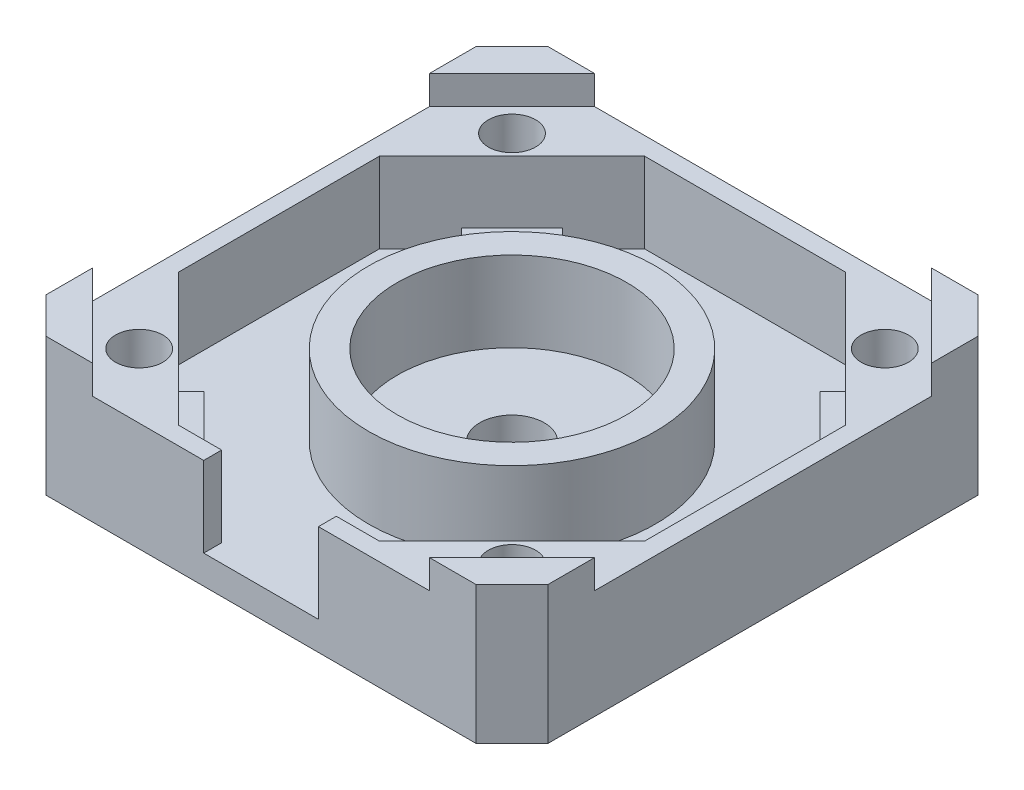
SolidWorks part; units mm, degrees
ref_plane "Front Plane" through (0, 0, 0) normal (0, 0, 1) x (1, 0, 0)
ref_plane "Top Plane" through (0, 0, 0) normal (0, 1, 0) x (1, 0, 0)
ref_plane "Right Plane" through (0, 0, 0) normal (1, 0, 0) x (0, 0, -1)
sketch "Sketch1" plane through (0, 0, 0) normal (0, 1, 0) x (1, 0, 0)
  line L1 (-17.5, -17.5) -> (17.5, -17.5)
  line L2 (-17.5, -17.5) -> (-17.5, 17.5)
  line L3 (-17.5, 17.5) -> (17.5, 17.5)
  line L4 (17.5, -17.5) -> (17.5, 17.5)
  line L5 (-17.5, -17.5) -> (17.5, 17.5) construction
  line L6 (-17.5, 17.5) -> (17.5, -17.5) construction
  point P0 (0, 0)
  dimension "D1" = 35
  dimension "D2" = 35
extrude "Boss-Extrude1" add sketch "Sketch1" along normal blind 9.6
sketch "Sketch2" plane through (0, 9.6, 0) normal (0, 1, 0) x (1, 0, 0)
  line L0 (0, 17.5) -> (0, -17.5) construction
  line L1 (17.5, 17.5) -> (-17.5, 17.5) construction
  line L2 (-17.5, -17.5) -> (17.5, -17.5) construction
  line L3 (-17.5, 0) -> (17.5, 0) construction
  line L4 (-17.5, 17.5) -> (-17.5, -17.5) construction
  line L5 (17.5, -17.5) -> (17.5, 17.5) construction
  line L6 (7, 16.25) -> (-7, 16.25)
  line L7 (-7, 16.25) -> (-16.25, 7)
  line L8 (-16.25, 7) -> (-16.25, -7)
  line L9 (7, 16.25) -> (16.25, 7)
  line L10 (16.25, 7) -> (16.25, -7)
  line L11 (7, -16.25) -> (16.25, -7)
  line L12 (7, -16.25) -> (4, -16.25)
  line L13 (-7, -16.25) -> (-16.25, -7)
  line L14 (-4, -16.25) -> (-4, -17.5)
  line L15 (-4, -17.5) -> (4, -17.5)
  line L16 (4, -16.25) -> (4, -17.5)
  line L17 (-4, -16.25) -> (-7, -16.25)
  circle A0 centre (0, 0) radius 8
  circle A1 centre (0, 0) radius 10
  point P21 (0, 16.25)
  point P24 (16.25, 0)
  point P27 (-16.25, 0)
  line M18 (-17.5, -17.5) -> (17.5, -17.5)
  dimension "D1" = 16
  dimension "D2" = 20
  dimension "D3" = 7
  dimension "D4" = 1.25
  dimension "D5" = 7
  dimension "D6" = 1.25
  dimension "D7" = 4
extrude "Cut-Extrude1" cut sketch "Sketch2" against normal blind 7.6 contours L17 L14 L16 L12 L11 L10 L9 L6 L7 L8 L13 A1 M18 | A0
sketch "Sketch3" plane through (0, 9.6, 0) normal (0, 1, 0) x (1, 0, 0)
  line L0 (0, 17.5) -> (0, -17.5) construction
  line L1 (17.5, 17.5) -> (-17.5, 17.5) construction
  line L2 (-4, -17.5) -> (4, -17.5) construction
  line L3 (-17.5, 0) -> (17.5, 0) construction
  line L4 (-17.5, 17.5) -> (-17.5, -17.5) construction
  line L5 (17.5, -17.5) -> (17.5, 17.5) construction
  line L6 (11.75, 17.5) -> (-11.75, 17.5)
  line L7 (-11.75, 17.5) -> (-17.5, 11.75)
  line L8 (-17.5, 11.75) -> (-17.5, -11.75)
  line L9 (11.75, 17.5) -> (17.5, 11.75)
  line L10 (17.5, 11.75) -> (17.5, -11.75)
  line L11 (11.75, -17.5) -> (17.5, -11.75)
  line L12 (11.75, -17.5) -> (-11.75, -17.5)
  line L13 (-11.75, -17.5) -> (-17.5, -11.75)
  dimension "D1" = 11.75
  dimension "D2" = 11.75
extrude "Cut-Extrude2" cut sketch "Sketch3" against normal blind 2
chamfer "Chamfer1" distance 2.5 angle 45 4 edges at (-17.5, 4.8, 17.5) (17.5, 4.8, 17.5) (17.5, 4.8, -17.5) (-17.5, 4.8, -17.5)
sketch "Sketch4" plane through (0, 7.6, 0) normal (0, 1, 0) x (1, 0, 0)
  line L0 (-17.5, 0) -> (17.5, 0) construction
  line L1 (-17.5, 11.75) -> (-17.5, -11.75) construction
  line L2 (17.5, -11.75) -> (17.5, 11.75) construction
  line L3 (0, 17.5) -> (0, -17.5) construction
  line L4 (11.75, 17.5) -> (-11.75, 17.5) construction
  line L5 (-4, -17.5) -> (4, -17.5) construction
  circle A0 centre (-13, 13) radius 1.65
  circle A1 centre (13, 13) radius 1.65
  circle A2 centre (13, -13) radius 1.65
  circle A3 centre (-13, -13) radius 1.65
  circle A4 centre (0, 0) radius 2.25
  dimension "D1" = 3.3
  dimension "D2" = 13
  dimension "D3" = 13
  dimension "D4" = 4.5
extrude "Cut-Extrude3" cut sketch "Sketch4" against normal through all
sketch "Sketch5" plane through (0, 0, 0) normal (0, -1, 0) x (1, 0, 0)
  line L0 (17.5, 0) -> (-17.5, 0) construction
  line L1 (17.5, 15) -> (17.5, -15) construction
  line L2 (-17.5, -15) -> (-17.5, 15) construction
  line L3 (0, 17.5) -> (0, -17.5) construction
  line L4 (-15, 17.5) -> (15, 17.5) construction
  line L5 (15, -17.5) -> (-15, -17.5) construction
  circle A0 centre (13, 13) radius 3
  circle A1 centre (13, -13) radius 3
  circle A2 centre (-13, -13) radius 3
  circle A3 centre (-13, 13) radius 3
  dimension "D1" = 6
extrude "Cut-Extrude4" cut sketch "Sketch5" against normal blind 2.5
sketch "Sketch6" plane through (0, 2, 0) normal (0, 1, 0) x (1, 0, 0)
  line L6 (17.5, 0) -> (-17.5, 0) construction
  line L7 (17.5, -11.75) -> (17.5, 11.75) construction
  line L8 (-17.5, 11.75) -> (-17.5, -11.75) construction
  line L9 (0, 17.5) -> (0, -17.5) construction
  line L10 (11.75, 17.5) -> (-11.75, 17.5) construction
  line L11 (-4, -17.5) -> (4, -17.5) construction
  line L24 (11.625, 11.625) -> (10.8787, 10.8787) construction
  line L25 (16.25, 7) -> (7, 16.25) construction
  line L26 (13.3928, 9.8572) -> (9.8572, 13.3928)
  line L27 (9.8572, 13.3928) -> (8.9733, 12.5089)
  line L28 (13.3928, 9.8572) -> (12.5089, 8.9733)
  line L29 (8.9733, 12.5089) -> (12.5089, 8.9733)
  line L30 (9.8572, -13.3928) -> (8.9733, -12.5089)
  line L31 (13.3928, -9.8572) -> (9.8572, -13.3928)
  line L32 (13.3928, -9.8572) -> (12.5089, -8.9733)
  line L33 (8.9733, -12.5089) -> (12.5089, -8.9733)
  line L34 (-13.3928, -9.8572) -> (-9.8572, -13.3928)
  line L35 (-13.3928, -9.8572) -> (-12.5089, -8.9733)
  line L36 (-8.9733, -12.5089) -> (-12.5089, -8.9733)
  line L37 (-9.8572, -13.3928) -> (-8.9733, -12.5089)
  line L38 (-9.8572, 13.3928) -> (-8.9733, 12.5089)
  line L39 (-13.3928, 9.8572) -> (-9.8572, 13.3928)
  line L40 (-13.3928, 9.8572) -> (-12.5089, 8.9733)
  line L41 (-8.9733, 12.5089) -> (-12.5089, 8.9733)
  arc A2 (10.0096, 13.2404) -> (13.2404, 10.0096) centre (13, 13) ccw construction
  dimension "D1" = 2.5
  dimension "D2" = 1.25
extrude "Boss-Extrude3" add sketch "Sketch6" along normal blind 1.25
